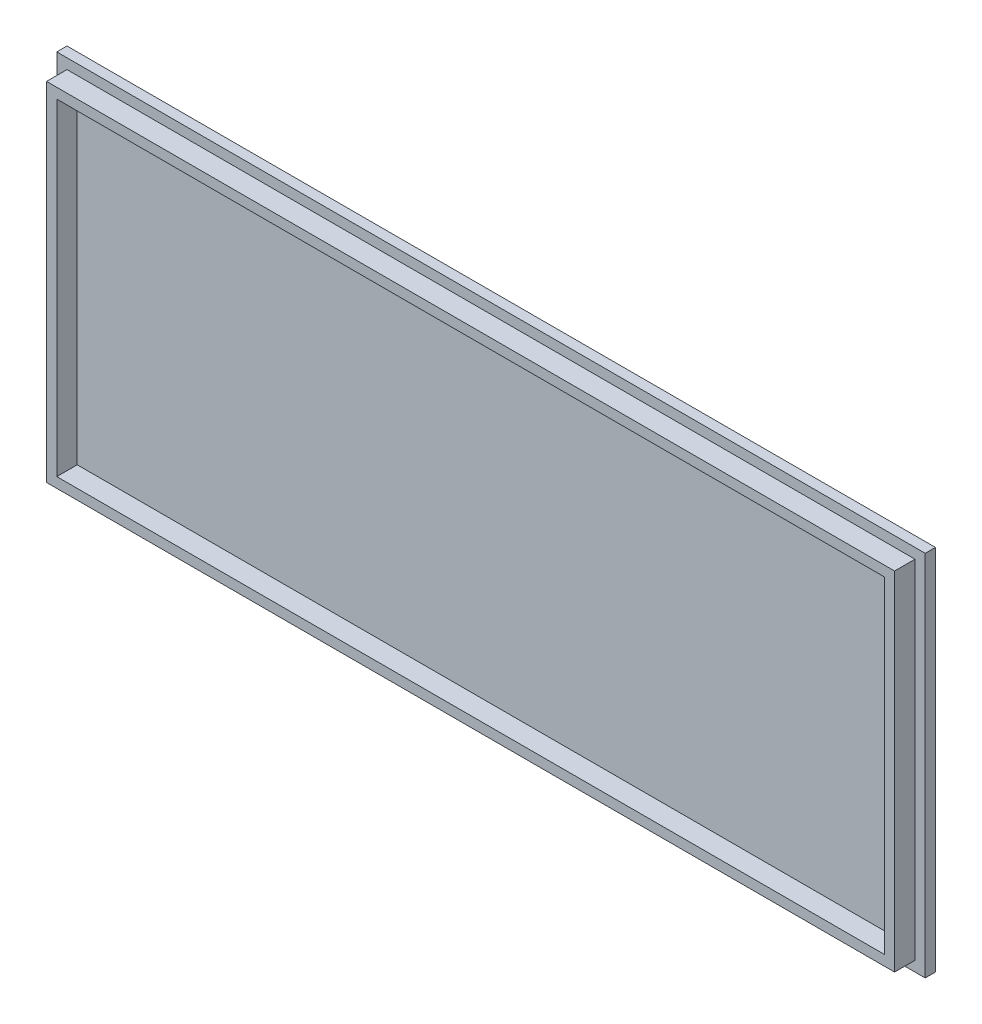
SolidWorks part; units mm, degrees
ref_plane "Ebene vorne" through (0, 0, 0) normal (0, 0, 1) x (1, 0, 0)
ref_plane "Ebene oben" through (0, 0, 0) normal (0, 1, 0) x (1, 0, 0)
ref_plane "Ebene rechts" through (0, 0, 0) normal (1, 0, 0) x (0, 0, -1)
sketch "Skizze1" plane through (0, 0, 0) normal (0, 0, 1) x (1, 0, 0)
  line L1 (-85, 36) -> (0, 36)
  line L2 (-85, 36) -> (-85, 0)
  line L3 (-85, 0) -> (0, 0)
  line L4 (0, 36) -> (0, 0)
  dimension "D1" = 85
  dimension "D2" = 36
extrude "Aufsatz-Linear austragen1" add sketch "Skizze1" along normal blind 1
sketch "Skizze2" plane through (0, 0, 1) normal (0, 0, 1) x (1, 0, 0)
  line L10 (-2, 2) -> (-2, 34)
  line L11 (-2, 34) -> (-83, 34)
  line L12 (-83, 34) -> (-83, 2)
  line L13 (-83, 2) -> (-2, 2)
  line L14 (-1, 1) -> (-1, 35)
  line L15 (-84, 1) -> (-1, 1)
  line L16 (-84, 35) -> (-84, 1)
  line L17 (-1, 35) -> (-84, 35)
  line L18 (-1, 1) -> (-1, 35)
  line L19 (-84, 1) -> (-1, 1)
  line L20 (-84, 35) -> (-84, 1)
  line L21 (-1, 35) -> (-84, 35)
  dimension "D1" = 1
  dimension "D2" = 1
extrude "Aufsatz-Linear austragen2" add sketch "Skizze2" along normal blind 2
